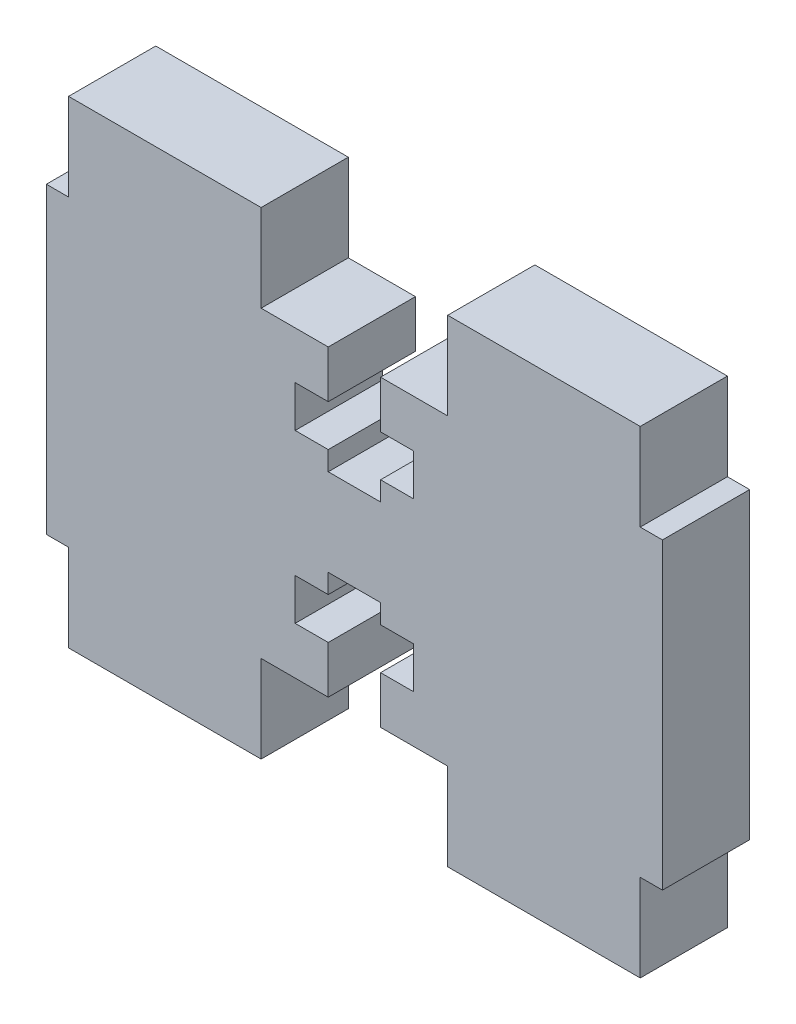
SolidWorks part; units mm, degrees
ref_plane "Front Plane" through (0, 0, 0) normal (0, 0, 1) x (1, 0, 0)
ref_plane "Top Plane" through (0, 0, 0) normal (0, 1, 0) x (1, 0, 0)
ref_plane "Right Plane" through (0, 0, 0) normal (1, 0, 0) x (0, 0, -1)
sketch "Sketch1" plane through (0, 0, 0) normal (0, 0, 1) x (1, 0, 0)
  line L0 (-19.15, 10.16) -> (-20.6375, 10.16)
  line L1 (6.25, -13.081) -> (19.15, -13.081) construction
  line L2 (20.6375, -10.16) -> (20.6375, 10.16)
  line L3 (20.6375, 10.16) -> (19.15, 10.16)
  line L4 (-20.6375, -10.16) -> (-20.6375, 10.16)
  line L5 (0, 10.16) -> (0, -10.16) construction
  line L6 (20.6375, 0) -> (-20.6375, 0) construction
  line L7 (-6.25, 16.002) -> (-19.15, 16.002)
  line L8 (-6.25, 16.002) -> (-6.25, 10.16)
  line L9 (-1.7526, 4.2069) -> (-3.9687, 4.2069)
  line L10 (-19.15, 16.002) -> (-19.15, 10.16)
  line L11 (-12.7, 10.16) -> (-12.7, 16.002) construction
  line L12 (-6.25, 13.081) -> (-19.15, 13.081) construction
  line L13 (-1.7526, 10.16) -> (-6.25, 10.16)
  line L14 (1.7526, 6.985) -> (1.7526, 10.16)
  line L15 (12.7, 10.16) -> (12.7, 16.002) construction
  line L16 (-1.7526, 6.985) -> (-1.7526, 10.16)
  line L17 (0, 10.16) -> (0, 6.985) construction
  line L18 (1.7526, 8.5725) -> (-1.7526, 8.5725) construction
  line L19 (3.9688, 4.2069) -> (1.7526, 4.2069)
  line L20 (3.9688, 4.2069) -> (3.9688, 6.985)
  line L21 (3.9688, 6.985) -> (1.7526, 6.985)
  line L22 (-3.9687, 4.2069) -> (-3.9687, 6.985)
  line L23 (0, 6.985) -> (0, 4.2069) construction
  line L24 (3.9688, 5.5959) -> (-3.9687, 5.5959) construction
  line L25 (1.7526, 2.9179) -> (-1.7526, 2.9179)
  line L26 (1.7526, 2.9179) -> (1.7526, 4.2069)
  line L27 (-1.7526, 6.985) -> (-3.9687, 6.985)
  line L28 (-1.7526, 2.9179) -> (-1.7526, 4.2069)
  line L29 (0, 4.2069) -> (0, 2.9179) construction
  line L30 (1.7526, 3.5624) -> (-1.7526, 3.5624) construction
  line L31 (19.15, 16.002) -> (19.15, 10.16)
  line L32 (6.25, 16.002) -> (6.25, 10.16)
  line L33 (6.25, 13.081) -> (19.15, 13.081) construction
  line L34 (6.25, 16.002) -> (19.15, 16.002)
  line L35 (6.25, 10.16) -> (1.7526, 10.16)
  line L36 (12.7, -10.16) -> (12.7, -16.002) construction
  line L37 (-6.25, -13.081) -> (-19.15, -13.081) construction
  line L38 (-12.7, -10.16) -> (-12.7, -16.002) construction
  line L39 (-1.7526, -10.16) -> (-6.25, -10.16)
  line L40 (6.25, -16.002) -> (19.15, -16.002)
  line L41 (6.25, -16.002) -> (6.25, -10.16)
  line L42 (19.15, -16.002) -> (19.15, -10.16)
  line L43 (6.25, -10.16) -> (1.7526, -10.16)
  line L44 (-19.15, -16.002) -> (-19.15, -10.16)
  line L45 (-6.25, -16.002) -> (-6.25, -10.16)
  line L46 (-6.25, -16.002) -> (-19.15, -16.002)
  line L47 (20.6375, -10.16) -> (19.15, -10.16)
  line L48 (-19.15, -10.16) -> (-20.6375, -10.16)
  line L49 (1.7526, -3.5624) -> (-1.7526, -3.5624) construction
  line L50 (0, -4.2069) -> (0, -2.9179) construction
  line L51 (3.9688, -5.5959) -> (-3.9687, -5.5959) construction
  line L52 (0, -6.985) -> (0, -4.2069) construction
  line L53 (1.7526, -8.5725) -> (-1.7526, -8.5725) construction
  line L54 (0, -10.16) -> (0, -6.985) construction
  line L55 (-1.7526, -2.9179) -> (-1.7526, -4.2069)
  line L56 (-1.7526, -6.985) -> (-3.9687, -6.985)
  line L57 (1.7526, -2.9179) -> (1.7526, -4.2069)
  line L58 (1.7526, -2.9179) -> (-1.7526, -2.9179)
  line L59 (-3.9687, -4.2069) -> (-3.9687, -6.985)
  line L60 (3.9688, -6.985) -> (1.7526, -6.985)
  line L61 (3.9688, -4.2069) -> (3.9688, -6.985)
  line L62 (3.9688, -4.2069) -> (1.7526, -4.2069)
  line L63 (-1.7526, -6.985) -> (-1.7526, -10.16)
  line L64 (1.7526, -6.985) -> (1.7526, -10.16)
  line L65 (-1.7526, -4.2069) -> (-3.9687, -4.2069)
  point P0 (0, 0)
  point P4 (-12.7, 13.081)
  point P11 (0, 8.5725)
  point P18 (0, 5.5959)
  point P28 (0, 3.5624)
  point P49 (12.7, 13.081)
  point P70 (12.7, -13.081)
  point P71 (-12.7, -13.081)
  point P91 (0, -3.5624)
  point P92 (0, -5.5959)
  point P93 (0, -8.5725)
  dimension "D1" = 41.275
  dimension "D2" = 20.32
  dimension "D3" = 12.9
  dimension "D4" = 12.7
  dimension "D5" = 5.842
  dimension "D6" = 3.5052
  dimension "D7" = 7.9375
  dimension "D8" = 2.7781
  dimension "D9" = 3.175
  dimension "D10" = 1.289
extrude "Boss-Extrude1" add sketch "Sketch1" along normal blind 5.842
